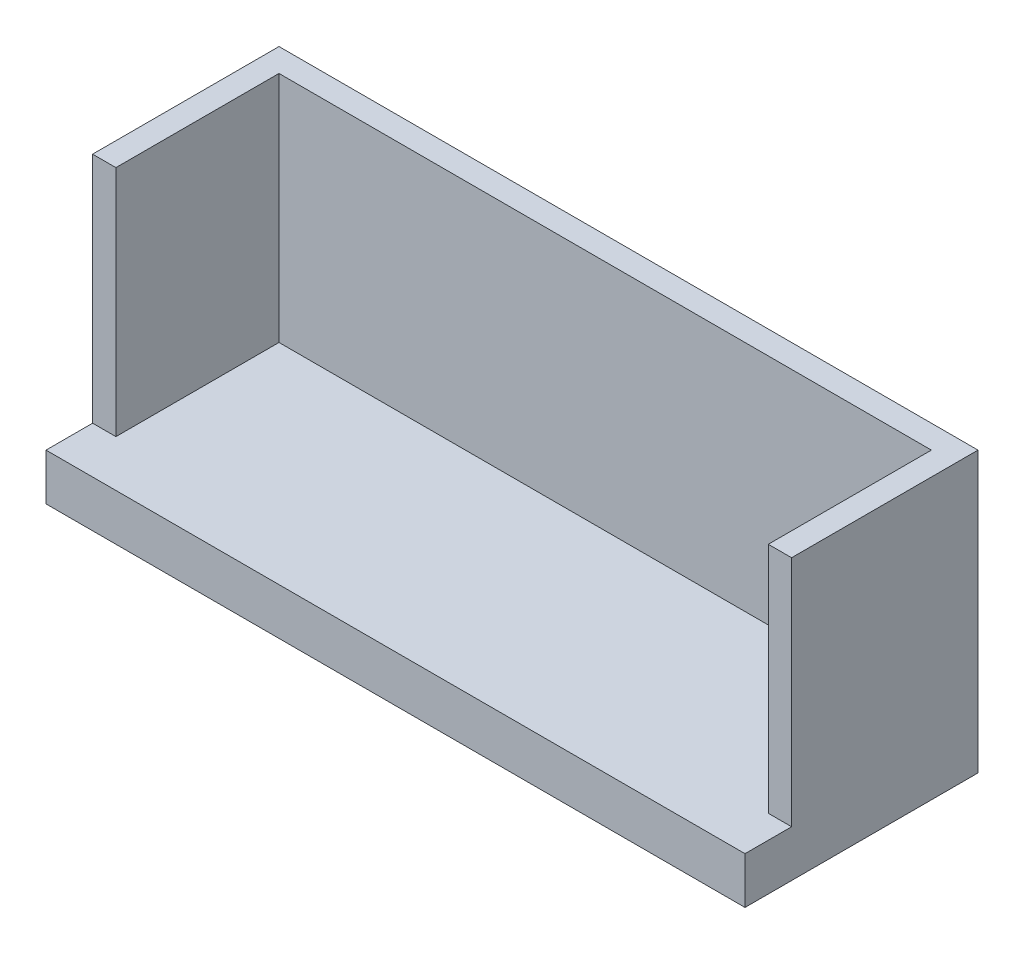
SolidWorks part; units mm, degrees
ref_plane "前视基准面" through (0, 0, 0) normal (0, 0, 1) x (1, 0, 0)
ref_plane "上视基准面" through (0, 0, 0) normal (0, 1, 0) x (1, 0, 0)
ref_plane "右视基准面" through (0, 0, 0) normal (1, 0, 0) x (0, 0, -1)
other "Configuration Table"
sketch "草图1" plane through (0, 0, 0) normal (0, 1, 0) x (1, 0, 0)
  line L1 (-7.5, 2.5) -> (7.5, 2.5)
  line L2 (-7.5, 2.5) -> (-7.5, -2.5)
  line L3 (-7.5, -2.5) -> (7.5, -2.5)
  line L4 (7.5, 2.5) -> (7.5, -2.5)
  line L5 (-7.5, 2.5) -> (7.5, -2.5) construction
  line L6 (-7.5, -2.5) -> (7.5, 2.5) construction
  point P0 (0, 0)
  dimension "D1" = 15
  dimension "D2" = 5
extrude "凸台-拉伸1" add sketch "草图1" along normal blind 1
sketch "草图3" plane through (0, 1, 0) normal (0, 1, 0) x (1, 0, 0)
  line L0 (-7.5, -1.5) -> (-7, -1.5)
  line L1 (-7.5, 2.5) -> (-7.5, -2.5) construction
  line L2 (-7, -1.5) -> (-7, 2)
  line L3 (-7, 2) -> (7, 2)
  line L4 (7, 2) -> (7, -1.5)
  line L5 (7, -1.5) -> (7.5, -1.5)
  line L6 (7.5, -2.5) -> (7.5, 2.5) construction
  line L7 (7.5, -1.5) -> (7.5, 2.5)
  line L8 (7.5, 2.5) -> (-7.5, 2.5)
  line L9 (-7.5, 2.5) -> (-7.5, -1.5)
  line L10 (-7.5, -2.5) -> (7.5, -2.5) construction
  dimension "D1" = 0.5
  dimension "D2" = 0.5
  dimension "D3" = 0.5
  dimension "D4" = 1
  dimension "D5" = 1
extrude "凸台-拉伸2" add sketch "草图3" along normal blind 5
